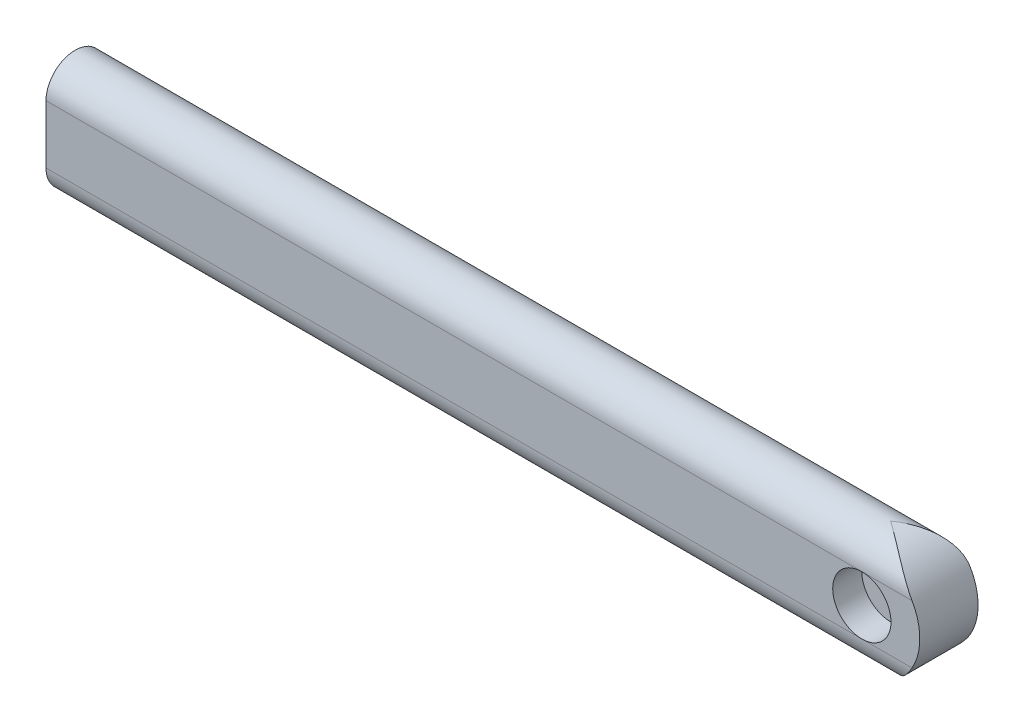
SolidWorks part; units mm, degrees
ref_plane "Front Plane" through (0, 0, 0) normal (0, 0, 1) x (1, 0, 0)
ref_plane "Top Plane" through (0, 0, 0) normal (0, 1, 0) x (1, 0, 0)
ref_plane "Right Plane" through (0, 0, 0) normal (1, 0, 0) x (0, 0, -1)
other "Center of Mass"
sketch "Sketch1" plane through (0, 0, 0) normal (1, 0, 0) x (0, 0, -1)
  line L2 (-50, 50) -> (-50, -50)
  line L4 (50, 50) -> (50, -50)
  arc A0 (50, 50) -> (-50, 50) centre (0, 50) ccw
  arc A1 (-50, -50) -> (50, -50) centre (0, -50) ccw
  point P0 (0, 0)
  dimension "D3" = 100
  dimension "D1" = 100
  dimension "D2" = 100
extrude "Boss-Extrude1" add sketch "Sketch1" against normal blind 1500
sketch "Sketch2" plane through (0, 0, 50) normal (0, 0, 1) x (1, 0, 0)
  line L4 (-100.5, 100) -> (0, 100)
  line L5 (0, 100) -> (0, -100)
  line L6 (0, -100) -> (-100.5, -100)
  arc A1 (-100.5, -100) -> (-100.5, 100) centre (-100.5, 0) ccw
  dimension "D1" = 100.5
extrude "Cut-Extrude1" cut sketch "Sketch2" against normal blind 100
sketch "Sketch3" plane through (0, 0, 50) normal (0, 0, 1) x (1, 0, 0)
  circle A0 centre (-100, 0) radius 50
  dimension "D1" = 100
  dimension "D2" = 100
extrude "Cut-Extrude2" cut sketch "Sketch3" against normal blind 50
sketch "Sketch4" plane through (-1500, 0, 0) normal (-1, 0, 0) x (0, 0, 1)
  circle A0 centre (0, 50) radius 25
  circle A1 centre (0, -50) radius 25
  dimension "D1" = 50
  dimension "D2" = 50
  dimension "D3" = 50
  dimension "D4" = 50
extrude "Cut-Extrude3" cut sketch "Sketch4" against normal blind 25
